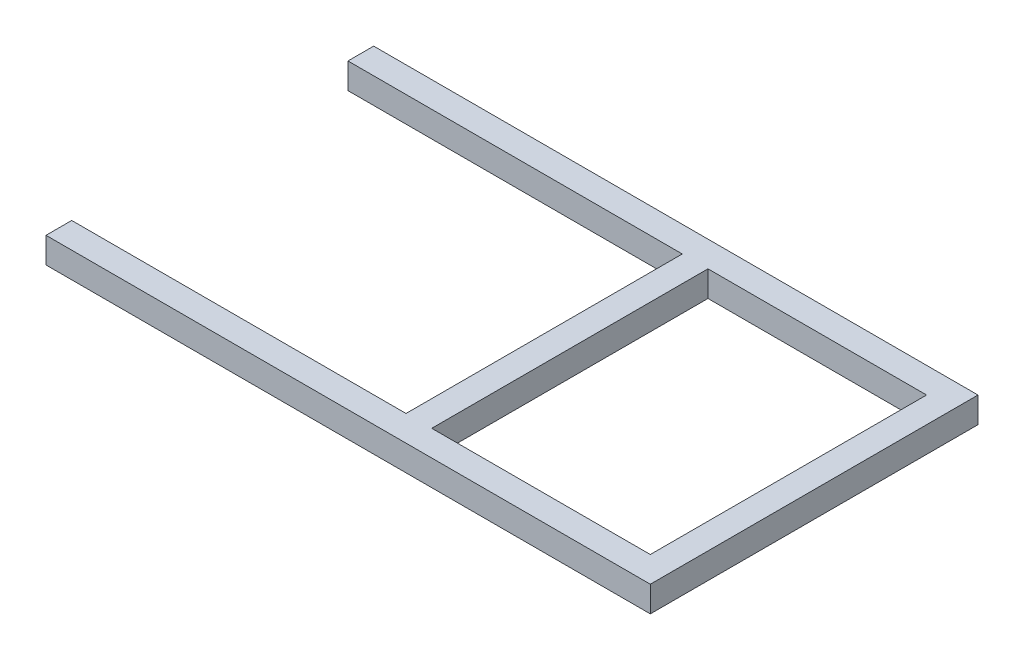
SolidWorks part; units mm, degrees
ref_plane "Front Plane" through (0, 0, 0) normal (0, 0, 1) x (1, 0, 0)
ref_plane "Top Plane" through (0, 0, 0) normal (0, 1, 0) x (1, 0, 0)
ref_plane "Right Plane" through (0, 0, 0) normal (1, 0, 0) x (0, 0, -1)
sketch "Sketch1" plane through (0, 0, 0) normal (0, 1, 0) x (1, 0, 0)
  line L1 (-10, 127.425) -> (10, 127.425)
  line L2 (-10, 127.425) -> (-10, -127.425)
  line L3 (-10, -127.425) -> (10, -127.425)
  line L4 (10, 127.425) -> (10, -127.425)
  line L5 (-10, 127.425) -> (10, -127.425) construction
  line L6 (-10, -127.425) -> (10, 127.425) construction
  point P0 (0, 0)
  dimension "D1" = 20
  dimension "D2" = 254.85
extrude "Boss-Extrude1" add sketch "Sketch1" along normal blind 20
sketch "Sketch3" plane through (-10, 0, 0) normal (-1, 0, 0) x (0, 0, 1)
  line L0 (-127.425, 0) -> (127.425, 0) construction
  line L1 (127.425, 20) -> (107.425, 20)
  line L2 (127.425, 20) -> (127.425, 0)
  line L3 (127.425, 0) -> (107.425, 0)
  line L4 (107.425, 20) -> (107.425, 0)
  line L5 (-127.425, 20) -> (-127.425, 0) construction
  line L6 (-127.425, 0) -> (-107.425, 0)
  line L7 (-127.425, 0) -> (-127.425, 20)
  line L8 (-127.425, 20) -> (-107.425, 20)
  line L9 (-107.425, 0) -> (-107.425, 20)
  line L10 (-127.425, 20) -> (127.425, 20) construction
  dimension "D1" = 20
  dimension "D2" = 20
extrude "Boss-Extrude2" add sketch "Sketch3" along normal blind 450
sketch "Sketch5" plane through (0, 0, -107.425) normal (0, 0, 1) x (1, 0, 0)
  line L0 (-460, 20) -> (-10, 20) construction
  line L1 (-200, 20) -> (-180, 20)
  line L2 (-200, 20) -> (-200, 0)
  line L3 (-200, 0) -> (-180, 0)
  line L4 (-180, 20) -> (-180, 0)
  line L5 (-460, 0) -> (-10, 0) construction
  line L6 (-10, 0) -> (-10, 20) construction
  point P8 (-180, 10)
  dimension "D1" = 20
  dimension "D2" = 170
extrude "Boss-Extrude4" add sketch "Sketch5" along normal blind 214.85
